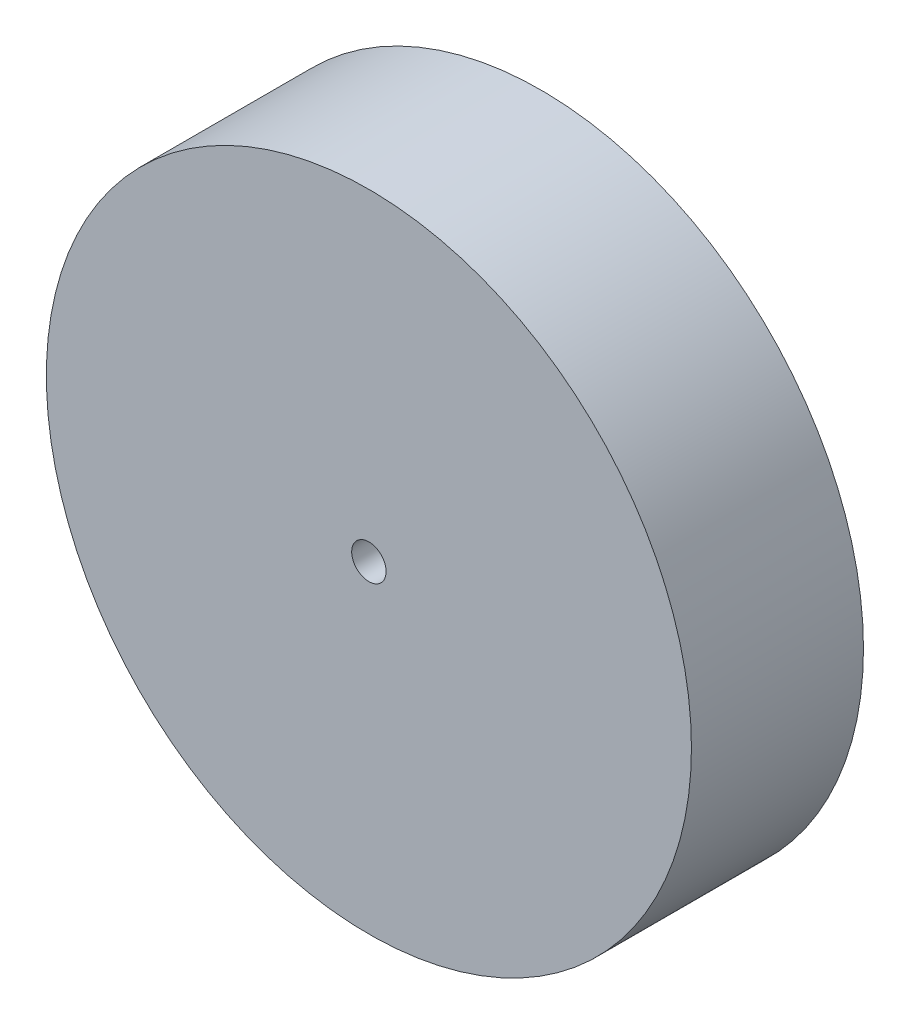
SolidWorks part; units mm, degrees
ref_plane "Front Plane" through (0, 0, 0) normal (0, 0, 1) x (1, 0, 0)
ref_plane "Top Plane" through (0, 0, 0) normal (0, 1, 0) x (1, 0, 0)
ref_plane "Right Plane" through (0, 0, 0) normal (1, 0, 0) x (0, 0, -1)
sketch "草圖1" plane through (0, 0, 0) normal (0, 0, 1) x (1, 0, 0)
  circle A0 centre (0, 0) radius 37.5
  circle A1 centre (0, 0) radius 2
  dimension "D1" = 4
  dimension "D2" = 75
extrude "填料-伸長1" add sketch "草圖1" along normal blind 20
